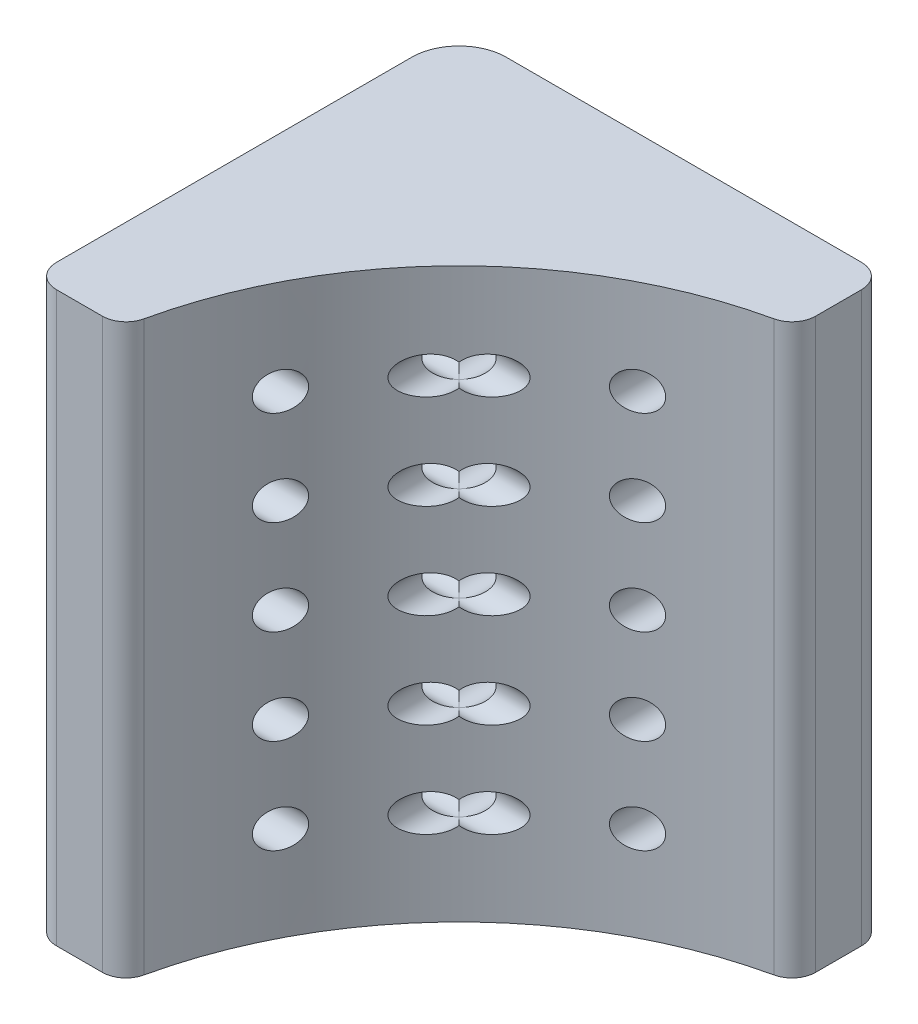
SolidWorks part; units mm, degrees
ref_plane "Front Plane" through (0, 0, 0) normal (0, 0, 1) x (1, 0, 0)
ref_plane "Top Plane" through (0, 0, 0) normal (0, 1, 0) x (1, 0, 0)
ref_plane "Right Plane" through (0, 0, 0) normal (1, 0, 0) x (0, 0, -1)
sketch "Sketch2" plane through (0, 0, 0) normal (0, 1, 0) x (1, 0, 0)
  line L0 (0, 0) -> (0, -53.975)
  line L1 (0, 0) -> (53.975, 0)
  line L2 (57.15, -3.175) -> (57.15, -11.935)
  line L3 (3.175, -57.15) -> (9.3269, -57.15)
  circle A0 centre (66.675, -66.675) radius 55.5625
  circle A1 centre (53.975, -3.175) radius 3.175
  circle A2 centre (53.975, -9.3269) radius 3.175
  circle A3 centre (3.175, -53.975) radius 3.175
  circle A4 centre (9.3269, -53.975) radius 3.175
  circle A5 centre (6.35, -6.35) radius 6.35
  dimension "D2" = 111.125
  dimension "D3" = 6.35
  dimension "D6" = 6.35
  dimension "D7" = 12.7
  dimension "D1" = 53.975
  dimension "D4" = 66.675
  dimension "D5" = 66.675
extrude "Boss-Extrude1" add sketch "Sketch2" along normal blind 76.2 contours A4 A0 A2 A1 L1 L0 A3 | A4 A3 | A4 A3 L3 | A4 A3 | A2 A1 | A2 L2 A1 | A2 A1 | A3 A4 | A1 A2 | A5
sketch "Sketch3" plane through (0, 0, 0) normal (-1, 0, 0) x (0, 0, 1)
  line L0 (6.35, 0) -> (53.975, 0) construction
  line L1 (6.35, 76.2) -> (6.35, 0) construction
  circle A0 centre (25.4, 12.7) radius 2.4892
  circle A1 centre (41.275, 12.7) radius 2.4892
  circle A2 centre (41.275, 25.4) radius 2.4892
  circle A3 centre (41.275, 38.1) radius 2.4892
  circle A4 centre (41.275, 50.8) radius 2.4892
  circle A5 centre (41.275, 63.5) radius 2.4892
  circle A6 centre (25.4, 25.4) radius 2.4892
  circle A7 centre (25.4, 38.1) radius 2.4892
  circle A8 centre (25.4, 50.8) radius 2.4892
  circle A9 centre (25.4, 63.5) radius 2.4892
  point P6 (0, 0)
  point P7 (43.2253, 26.0842)
  dimension "D1" = 4.9784
  dimension "D2" = 12.7
  dimension "D3" = 19.05
  dimension "D6" = 12.7
  dimension "D7" = 15.875
  dimension "D4" = 2
  dimension "D5" = 5
extrude "Cut-Extrude1" cut sketch "Sketch3" against normal blind 76.2
sketch "Sketch4" plane through (0, 0, 0) normal (0, 0, -1) x (-1, 0, 0)
  line L0 (-6.35, 0) -> (-53.975, 0) construction
  line L1 (-6.35, 76.2) -> (-6.35, 0) construction
  circle A0 centre (-25.4, 12.7) radius 2.4892
  circle A1 centre (-41.275, 12.7) radius 2.4892
  circle A2 centre (-41.275, 25.4) radius 2.4892
  circle A3 centre (-41.275, 38.1) radius 2.4892
  circle A4 centre (-41.275, 50.8) radius 2.4892
  circle A5 centre (-41.275, 63.5) radius 2.4892
  circle A6 centre (-25.4, 25.4) radius 2.4892
  circle A7 centre (-25.4, 38.1) radius 2.4892
  circle A8 centre (-25.4, 50.8) radius 2.4892
  circle A9 centre (-25.4, 63.5) radius 2.4892
  point P6 (0, 0)
  dimension "D1" = 4.9784
  dimension "D2" = 12.7
  dimension "D3" = 19.05
  dimension "D6" = 15.875
  dimension "D7" = 12.7
  dimension "D4" = 2
  dimension "D5" = 5
extrude "Cut-Extrude2" cut sketch "Sketch4" against normal blind 76.2
